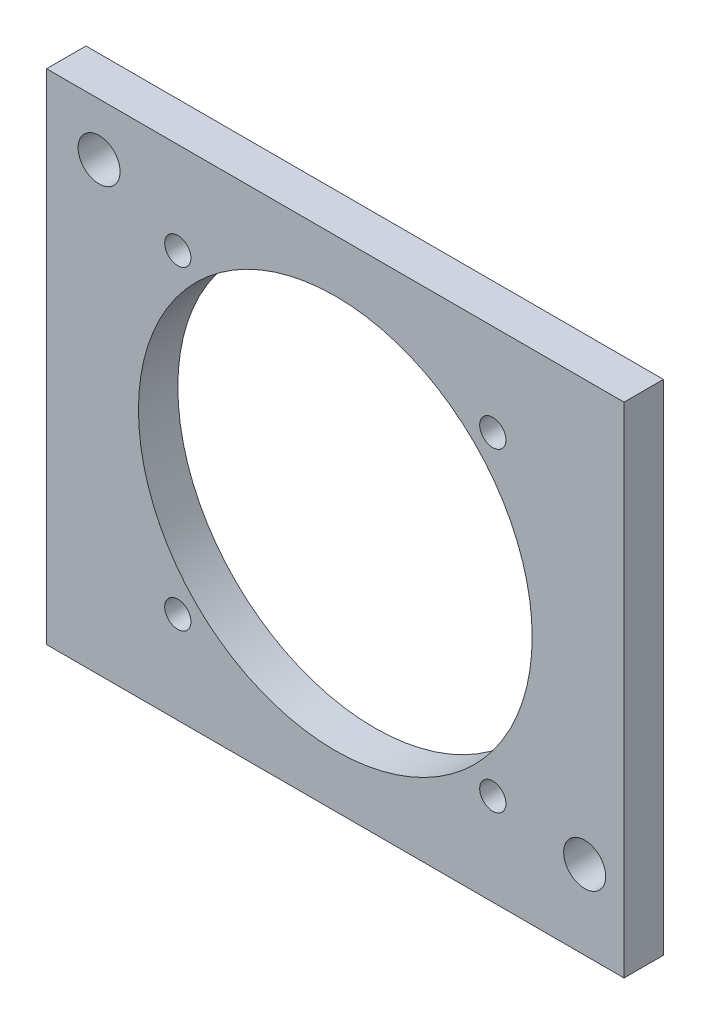
SolidWorks part; units mm, degrees
ref_plane "Ön Düzlem" through (0, 0, 0) normal (0, 0, 1) x (1, 0, 0)
ref_plane "Üst Düzlem" through (0, 0, 0) normal (0, 1, 0) x (1, 0, 0)
ref_plane "Sağ Düzlem" through (0, 0, 0) normal (1, 0, 0) x (0, 0, -1)
sketch "Sketch1" plane through (0, 0, 0) normal (0, 0, 1) x (1, 0, 0)
  line L1 (-110, -95) -> (110, -95)
  line L2 (-110, -95) -> (-110, 95)
  line L3 (-110, 95) -> (110, 95)
  line L4 (110, -95) -> (110, 95)
  line L5 (-110, -95) -> (110, 95) construction
  line L6 (-110, 95) -> (110, -95) construction
  point P0 (0, 0)
  dimension "D1" = 190
  dimension "D2" = 220
extrude "Boss-Extrude1" add sketch "Sketch1" along normal blind 15
sketch "Sketch2" plane through (0, 0, 15) normal (0, 0, 1) x (1, 0, 0)
  line L0 (-110, 95) -> (-110, -95) construction
  line L1 (-60, -60) -> (60, -60) construction
  line L2 (-60, -60) -> (-60, 60) construction
  line L3 (-60, 60) -> (60, 60) construction
  line L4 (60, -60) -> (60, 60) construction
  line L5 (-60, -60) -> (60, 60) construction
  line L6 (-60, 60) -> (60, -60) construction
  line L7 (110, 95) -> (-110, 95) construction
  line L8 (0, 0) -> (-124.702, 0) construction
  line L9 (110, -95) -> (110, 95) construction
  line L10 (-110, -95) -> (110, -95) construction
  circle A0 centre (0, 0) radius 75
  circle A1 centre (-90, 75) radius 8
  circle A2 centre (95, -65) radius 8
  circle A3 centre (-60, 60) radius 5
  circle A4 centre (60, 60) radius 5
  circle A5 centre (60, -60) radius 5
  circle A6 centre (-60, -60) radius 5
  dimension "D1" = 150
  dimension "D3" = 16
  dimension "D6" = 10
  dimension "D2" = 120
  dimension "D4" = 20
  dimension "D5" = 20
  dimension "D7" = 15
  dimension "D8" = 30
extrude "Cut-Extrude1" cut sketch "Sketch2" against normal up to surface (15 mm away) up to face at (0, 0, 0)
